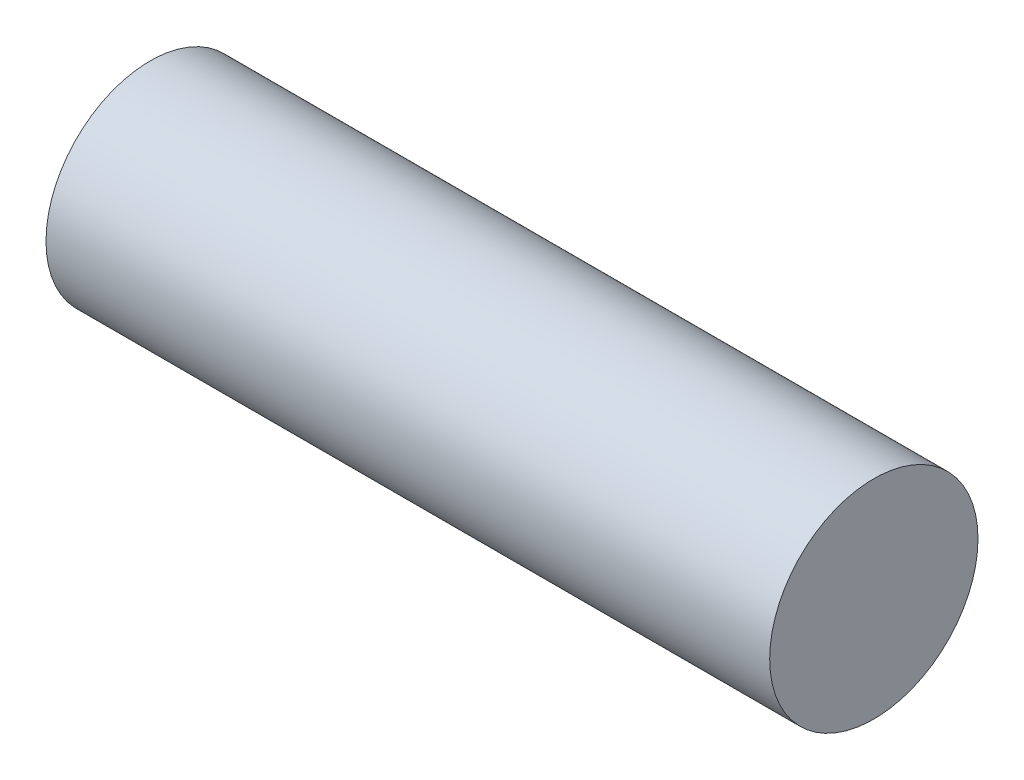
SolidWorks part; units mm, degrees
ref_plane "前视基准面" through (0, 0, 0) normal (0, 0, 1) x (1, 0, 0)
ref_plane "上视基准面" through (0, 0, 0) normal (0, 1, 0) x (1, 0, 0)
ref_plane "右视基准面" through (0, 0, 0) normal (1, 0, 0) x (0, 0, -1)
sketch "草图2" plane through (0, 0, 0) normal (1, 0, 0) x (0, 0, -1)
  circle A0 centre (0, 0) radius 9.5
extrude "凸台-拉伸1" add sketch "草图2" along normal blind 66
